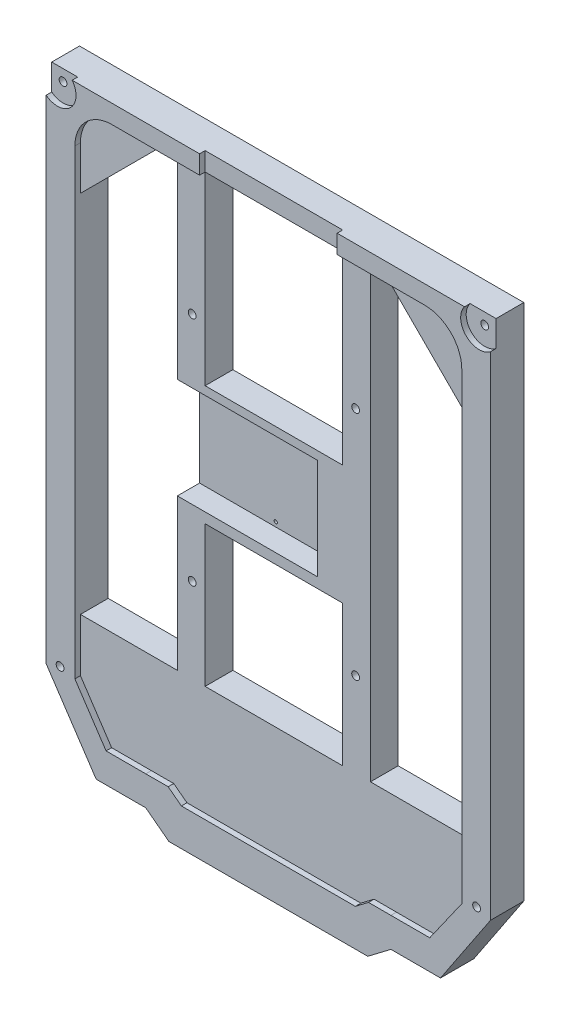
SolidWorks part; units mm, degrees
ref_plane "Front Plane" through (0, 0, 0) normal (0, 0, 1) x (1, 0, 0)
ref_plane "Top Plane" through (0, 0, 0) normal (0, 1, 0) x (1, 0, 0)
ref_plane "Right Plane" through (0, 0, 0) normal (1, 0, 0) x (0, 0, -1)
ref_plane "Plan1" through (0, 0, 30) normal (0, 0, 1) x (1, 0, 0)
sketch "Esquisse1" plane through (0, 0, 30) normal (0, 0, 1) x (1, 0, 0)
  line L0 (33.9438, -122.1178) -> (33.9438, 157.8822)
  line L1 (33.9438, 157.8822) -> (-206.0562, 157.8822)
  line L2 (-206.0562, 157.8822) -> (-206.0562, -122.1178)
  line L3 (-206.0562, -122.1178) -> (-179.0562, -162.6148)
  line L4 (-179.0562, -162.6148) -> (-152.2689, -162.6148)
  line L5 (-152.2689, -162.6148) -> (-139.751, -172.1178)
  line L6 (-139.751, -172.1178) -> (-32.3613, -172.1178)
  line L7 (-32.3613, -172.1178) -> (-19.8434, -162.6148)
  line L8 (-19.8434, -162.6148) -> (6.9438, -162.6148)
  line L9 (6.9438, -162.6148) -> (33.9438, -122.1178)
extrude "Boss.-Extru.1" add sketch "Esquisse1" against normal blind 30
sketch "Esquisse2" plane through (0, 0, 30) normal (0, 0, 1) x (1, 0, 0)
  line L0 (-123.2061, 157.8822) -> (-123.2061, 147.8822)
  line L1 (-123.2061, 147.8822) -> (-190.5562, 147.8822)
  line L2 (-190.5562, 147.8822) -> (-190.5562, -121.432)
  line L3 (-190.5562, -121.432) -> (-173.704, -146.7084)
  line L4 (-173.704, -146.7084) -> (-152.2689, -146.7084)
  line L5 (-152.2689, -146.7084) -> (-140.1758, -146.6851)
  line L6 (-140.1758, -146.6851) -> (-133.0195, -152.1178)
  line L7 (-133.0195, -152.1178) -> (-39.0928, -152.1178)
  line L8 (-39.0928, -152.1178) -> (-31.9365, -146.6851)
  line L9 (-31.9365, -146.6851) -> (-19.8434, -146.7084)
  line L10 (-19.8434, -146.7084) -> (1.1411, -146.7084)
  line L11 (1.1411, -146.7084) -> (18.4438, -122.1178)
  line L12 (18.4438, -122.1178) -> (18.4438, 147.8822)
  line L13 (18.4438, 147.8822) -> (-48.9062, 147.8822)
  line L14 (-48.9062, 147.8822) -> (-48.9062, 157.8822)
  line L15 (-48.9062, 157.8822) -> (-123.2061, 157.8822)
extrude "Enlèv. mat.-Extru.1" cut sketch "Esquisse2" against normal blind 15
sketch "Esquisse3" plane through (0, 0, 0) normal (0, 0, -1) x (-1, 0, 0)
  line L0 (162.5961, 137.8822) -> (162.5961, 147.8822)
  line L1 (162.5961, 147.8822) -> (190.5562, 147.8822)
  line L2 (190.5562, 147.8822) -> (190.5562, 118.9445)
  line L3 (190.5562, 118.9445) -> (180.5562, 118.9445)
  line L4 (180.5562, 118.9445) -> (180.5562, 137.8822)
  line L5 (180.5562, 137.8822) -> (162.5961, 137.8822)
extrude "Boss.-Extru.2" add sketch "Esquisse3" along normal blind 10
sketch "Esquisse4" plane through (0, 0, 0) normal (0, 0, -1) x (-1, 0, 0)
  line L0 (152.2689, -136.7084) -> (168.3524, -136.7084)
  line L1 (168.3524, -136.7084) -> (180.5562, -118.404)
  line L2 (180.5562, -118.404) -> (190.5562, -121.432)
  line L3 (190.5562, -121.432) -> (173.704, -146.7084)
  line L4 (173.704, -146.7084) -> (152.2689, -146.7084)
  line L5 (152.2689, -146.7084) -> (152.2689, -136.7084)
extrude "Boss.-Extru.3" add sketch "Esquisse4" along normal blind 10
sketch "Esquisse5" plane through (0, 0, 0) normal (0, 0, -1) x (-1, 0, 0)
  line L0 (-8.4438, 137.8822) -> (-8.4438, 118.9445)
  line L1 (-8.4438, 118.9445) -> (-18.4438, 118.9445)
  line L2 (-18.4438, 118.9445) -> (-18.4438, 147.8822)
  line L3 (-18.4438, 147.8822) -> (9.5162, 147.8822)
  line L4 (9.5162, 147.8822) -> (9.5162, 137.8822)
  line L5 (9.5162, 137.8822) -> (-8.4438, 137.8822)
extrude "Boss.-Extru.4" add sketch "Esquisse5" along normal blind 10
sketch "Esquisse6" plane through (0, 0, 0) normal (0, 0, -1) x (-1, 0, 0)
  line L0 (3.7599, -136.7084) -> (19.8434, -136.7084)
  line L1 (19.8434, -136.7084) -> (19.8434, -146.7084)
  line L2 (19.8434, -146.7084) -> (-1.1411, -146.7084)
  line L3 (-1.1411, -146.7084) -> (-18.4438, -122.1178)
  line L4 (-18.4438, -122.1178) -> (-8.4438, -118.404)
  line L5 (-8.4438, -118.404) -> (3.7599, -136.7084)
extrude "Boss.-Extru.5" add sketch "Esquisse6" along normal blind 10
hole_wizard "Diamètre du perçage Ø4.2 (4.2)1" positions "Esquisse8" profile "Esquisse7" hole size "Ø4.2" standard "Ansi Metric"
sketch "Esquisse8" plane through (0, 0, 30) normal (0, 0, 1) x (1, 0, 0)
  point P0 (26.4389, -119.6078)
  point P1 (-198.5512, -119.6078)
sketch "Esquisse7" plane through (26.4389, -119.6078, 30) normal (1, 0, 0) x (0, -1, 0)
  line L0 (0, 0) -> (0, 40)
  line L1 (0, 40) -> (2.1, 40)
  line L2 (2.1, 40) -> (2.1, 0)
  line L5 (2.1, 0) -> (0, 0)
  line L11 (0, -6.35) -> (0, 107.95) construction
  dimension "Diamètre du perçage jusqu'au prochain" = 4.2
  dimension "Profondeur du perçage jusqu'au prochain" = 40
hole_wizard "Chambrage pour vis à tête hexagonale M3.51" positions "Esquisse10" profile "Esquisse9" counterbore size "M3.5" standard "Ansi Metric"
sketch "Esquisse10" plane through (0, 0, 30) normal (0, 0, 1) x (1, 0, 0)
  point P0 (-199.9402, 151.7663)
  point P1 (27.8279, 151.7663)
sketch "Esquisse9" plane through (-199.9402, 151.7663, 30) normal (1, 0, 0) x (0, -1, 0)
  line L0 (0, 0) -> (0, 40)
  line L1 (0, 40) -> (2.1, 40)
  line L3 (2.1, 40) -> (2.1, 15)
  line L4 (2.1, 15) -> (10, 15)
  line L5 (10, 15) -> (10, 0)
  line L7 (10, 0) -> (0, 0)
  line L11 (0, -6.35) -> (0, 107.95) construction
  dimension "Diamètre du perçage jusqu'au prochain" = 4.2
  dimension "Profondeur du perçage jusqu'au prochain" = 40
  dimension "Diamètre du chambrage" = 20
  dimension "Profondeur du chambrage" = 15
fillet "Congé1" radius 10 2 edges at (-180.5562, 137.8822, -5) (8.4438, 137.8822, -5)
fillet "Congé2" radius 20 4 edges at (-190.5562, 147.8822, 22.5) (18.4438, 147.8822, -5) (18.4438, 147.8822, 22.5) (-190.5562, 147.8822, -5)
sketch "Esquisse11" plane through (0, 0, 15) normal (0, 0, 1) x (1, 0, 0)
  line L0 (-123.2061, 147.8822) -> (-123.2061, 47.8822)
  line L1 (-138.2061, 147.8822) -> (-138.2061, 57.8822)
  line L2 (-123.2061, 47.8822) -> (-190.5562, -22.4359)
  line L3 (-138.2061, 57.8822) -> (-190.5562, 3.2251)
  line L4 (-33.9062, 57.8822) -> (18.4438, 3.2251)
  line L5 (-33.9062, 147.8822) -> (-33.9062, 57.8822)
  line L6 (-48.9062, 147.8822) -> (-48.9062, 47.8822)
  line L7 (-48.9062, 47.8822) -> (18.4438, -22.4359)
  line L8 (-146.8811, 147.8822) -> (-190.5562, 104.2072)
  line L9 (18.4438, -22.4359) -> (18.4438, -92.768)
  line L10 (-25.2312, 147.8822) -> (18.4438, 104.2072)
  line L12 (-190.5562, -92.768) -> (18.4438, -92.768)
  line L13 (-190.5562, -22.4359) -> (-190.5562, -92.768)
  line L15 (18.4438, 95.5321) -> (18.4438, 3.2251)
  line L16 (-190.5562, 3.2251) -> (-190.5562, 95.5321)
  line L17 (-123.2061, 147.8822) -> (-48.9062, 147.8822)
  line L22 (-190.5562, 104.2072) -> (-190.5562, 95.5321)
  line L23 (-146.8811, 147.8822) -> (-138.2061, 147.8822)
  line L24 (-33.9062, 147.8822) -> (-25.2312, 147.8822)
  line L25 (18.4438, 104.2072) -> (18.4438, 95.5321)
  line L28 (-86.0562, 157.8822) -> (-86.0562, -181.6692) construction
  line L29 (-48.9062, 157.8822) -> (-123.2061, 157.8822) construction
extrude "Enlèv. mat.-Extru.2" cut sketch "Esquisse11" against normal through all
hole_wizard "Trou taraudé M5x0.81" positions "Esquisse3D1" profile "Esquisse12" tap size "M5x0.8" standard "Ansi Metric" end condition through all
sketch3d "Esquisse3D1"
  line L0 (-199.9402, 151.7663, 0) -> (-199.9402, 151.7663, 15) construction
  line L1 (27.8279, 151.7663, 0) -> (27.8279, 151.7663, 15) construction
  line L2 (26.4389, -119.6078, 0) -> (26.4389, -119.6078, 30) construction
  line L3 (-198.5512, -119.6078, 0) -> (-198.5512, -119.6078, 30) construction
  point P0 (-199.9402, 151.7663, 15)
  point P4 (27.8279, 151.7663, 15)
  point P8 (26.4389, -119.6078, 30)
  point P12 (-198.5512, -119.6078, 30)
sketch "Esquisse12" plane through (-199.9402, 151.7663, 15) normal (1, 0, 0) x (0, -1, 0)
  line L0 (0, 0) -> (0, 25)
  line L1 (0, 25) -> (2.1, 25)
  line L2 (2.1, 25) -> (2.1, 0)
  line L5 (2.1, 0) -> (0, 0)
  line L11 (0, -6.35) -> (0, 107.95) construction
  dimension "Diamètre du trou pour taraudage jusqu'au prochain" = 4.2
  dimension "Profondeur du trou pour taraudage jusqu'au prochain" = 25
cosmetic thread "Filetage de perçage1" parameters "D2"=5
cosmetic thread "Filetage de perçage2" parameters "D2"=5
cosmetic thread "Filetage de perçage5" parameters "D2"=5
cosmetic thread "Filetage de perçage6" parameters "D2"=5
sketch "Esquisse13" plane through (0, 0, 15) normal (0, 0, 1) x (1, 0, 0)
  line L0 (-48.9062, 47.8822) -> (-123.2061, 47.8822)
  line L1 (18.4438, -22.4359) -> (-48.9062, 47.8822) construction
  line L2 (-123.2061, 47.8822) -> (-148.9061, 21.0497)
  line L3 (-123.2061, 47.8822) -> (-190.5562, -22.4359) construction
  line L4 (-123.2061, 21.0497) -> (-48.9062, 21.0497)
  line L9 (-23.2063, 21.0497) -> (-48.9062, 47.8822)
  line L10 (18.4438, -49.2685) -> (18.4438, -22.4359)
  line L15 (-86.0562, 157.8822) -> (-86.0562, -186.9607) construction
  line L16 (-48.9062, 157.8822) -> (-123.2061, 157.8822) construction
  line L17 (-148.9061, 21.0497) -> (-190.5562, -22.4359)
  line L18 (-123.2061, 21.0497) -> (-190.5562, -49.2685)
  line L19 (-190.5562, 127.8822) -> (-190.5562, -121.432) construction
  line L20 (-190.5562, -49.2685) -> (-190.5562, -22.4359)
  line L21 (-23.2063, 21.0497) -> (18.4438, -22.4359)
  line L22 (-48.9062, 21.0497) -> (18.4438, -49.2685)
extrude "Boss.-Extru.6" add sketch "Esquisse13" against normal up to surface (15 mm away) up to face at (-11.2312, 92.2158, 0)
sketch "Esquisse14" plane through (0, 0, 30) normal (0, 0, 1) x (1, 0, 0)
  line L1 (-249.2636, 174.2987) -> (95.3604, 174.2987)
  line L2 (-249.2636, 174.2987) -> (-249.2636, -190.5575)
  line L3 (-249.2636, -190.5575) -> (95.3604, -190.5575)
  line L4 (95.3604, 174.2987) -> (95.3604, -190.5575)
extrude "Enlèv. mat.-Extru.3" cut sketch "Esquisse14" against normal blind 12
sketch "Esquisse15" plane through (0, 0, 15) normal (0, 0, 1) x (1, 0, 0)
  line L2 (-165.2407, 11.9495) -> (-165.2407, -16.6719)
  line L3 (-165.2407, -16.6719) -> (-10.3735, -16.6719)
  line L4 (-10.3735, 17.0806) -> (-10.3735, -16.6719)
  line L5 (-165.2407, 11.9495) -> (-140.9844, 36.2058)
  line L6 (-140.9844, 36.2058) -> (-29.4987, 36.2058)
  line L7 (-29.4987, 36.2058) -> (-10.3735, 17.0806)
extrude "Boss.-Extru.7" add sketch "Esquisse15" against normal up to surface (15 mm away)
sketch "Esquisse16" plane through (0, 0, 15) normal (0, 0, 1) x (1, 0, 0)
  line L0 (-86.0562, 157.8822) -> (-86.0562, -189.4449) construction
  line L1 (-48.9062, 157.8822) -> (-123.2061, 157.8822) construction
  line L3 (-109.5562, 43.3493) -> (-62.5562, 43.3493)
  line L4 (-109.5562, 43.3493) -> (-109.5562, -11.1507)
  line L5 (-109.5562, -11.1507) -> (-62.5562, -11.1507)
  line L6 (-62.5562, 43.3493) -> (-62.5562, -11.1507)
  line L7 (-109.5562, 43.3493) -> (-62.5562, -11.1507) construction
  line L8 (-109.5562, -11.1507) -> (-62.5562, 43.3493) construction
  point P4 (-86.0562, 16.0993)
  dimension "D1" = 54.5
  dimension "D2" = 47
extrude "Enlèv. mat.-Extru.4" cut sketch "Esquisse16" against normal blind 12
sketch "Esquisse17" plane through (0, 0, 3) normal (0, 0, 1) x (1, 0, 0)
  line L0 (-86.0562, 43.3493) -> (-86.0562, -11.1507) construction
  line L1 (-62.5562, 43.3493) -> (-109.5562, 43.3493) construction
  line L2 (-109.5562, -11.1507) -> (-62.5562, -11.1507) construction
  line L3 (-109.5562, 16.0993) -> (-62.5562, 16.0993) construction
  line L4 (-109.5562, 43.3493) -> (-109.5562, -11.1507) construction
  line L5 (-62.5562, -11.1507) -> (-62.5562, 43.3493) construction
  line L6 (-97.0612, 50.1985) -> (-97.0612, -29.2943) construction
  line L7 (-109.2012, 43.0993) -> (-62.9112, 43.0993)
  line L8 (-109.2012, 43.0993) -> (-109.2012, -10.9007)
  line L9 (-109.2012, -10.9007) -> (-62.9112, -10.9007)
  line L10 (-62.9112, 43.0993) -> (-62.9112, -10.9007) construction
  line L11 (-109.2012, 43.0993) -> (-62.9112, -10.9007) construction
  line L12 (-109.2012, -10.9007) -> (-62.9112, 43.0993) construction
  circle A4 centre (-65.1412, 16.0993) radius 2.23 construction
  circle A5 centre (-97.0612, -8.6707) radius 2.23 construction
  circle A6 centre (-97.0612, 40.8693) radius 2.23 construction
  circle A7 centre (-97.0612, 40.8693) radius 0.5
  circle A8 centre (-97.0612, -8.6707) radius 0.5
  circle A9 centre (-65.1412, 16.0993) radius 0.5
  point P12 (-86.0562, 16.0993)
  point P13 (-86.0562, 16.0993)
  dimension "D3" = 1
  dimension "D4" = 31.92
  dimension "D5" = 4.46
  dimension "D6" = 4.46
  dimension "D7" = 1
  dimension "D8" = 1
  dimension "D9" = 4.46
  dimension "D1" = 46.29
  dimension "D2" = 54
extrude "Enlèv. mat.-Extru.5" cut sketch "Esquisse17" against normal blind 12 contours A7 | A9 | A8
hole_wizard "Trou taraudé M2.2x0.451" positions "Esquisse3D2" profile "Esquisse18" tap size "M2.2x0.45" standard "Ansi Metric" end condition through all
sketch3d "Esquisse3D2"
  line L0 (-97.0612, 40.8693, 0) -> (-97.0612, 40.8693, 3) construction
  line L1 (-65.1412, 16.0993, 0) -> (-65.1412, 16.0993, 3) construction
  line L2 (-97.0612, -8.6707, 0) -> (-97.0612, -8.6707, 3) construction
  point P0 (-97.0612, 40.8693, 3)
  point P4 (-65.1412, 16.0993, 3)
  point P8 (-97.0612, -8.6707, 3)
sketch "Esquisse18" plane through (-97.0612, 40.8693, 3) normal (1, 0, 0) x (0, -1, 0)
  line L0 (0, 0) -> (0, 13)
  line L1 (0, 13) -> (0.875, 13)
  line L2 (0.875, 13) -> (0.875, 0)
  line L5 (0.875, 0) -> (0, 0)
  line L11 (0, -6.35) -> (0, 107.95) construction
  dimension "Diamètre du trou pour taraudage jusqu'au prochain" = 1.75
  dimension "Profondeur du trou pour taraudage jusqu'au prochain" = 13
cosmetic thread "Filetage de perçage7" parameters "D2"=2.2
cosmetic thread "Filetage de perçage8" parameters "D2"=2.2
cosmetic thread "Filetage de perçage9" parameters "D2"=2.2
sketch "Esquisse19" plane through (0, 0, 15) normal (0, 0, 1) x (1, 0, 0)
  line L0 (-138.2061, 57.8822) -> (-138.2061, -92.768)
  line L1 (-190.5562, -92.768) -> (18.4438, -92.768) construction
  line L2 (-123.2061, -92.768) -> (-123.2061, 67.1881) construction
  line L3 (-123.2061, 147.8822) -> (-123.2061, 47.8822) construction
  line L4 (-138.2061, -92.768) -> (-123.2061, -92.768)
  line L5 (-190.5562, -121.432) -> (-190.5562, 127.8822) construction
  line L6 (-190.5562, 57.8822) -> (-138.2061, 57.8822)
  line L7 (-190.5562, 57.8822) -> (-190.5562, -92.768)
  line L8 (-190.5562, -92.768) -> (-138.2061, -92.768)
  line L9 (-138.2061, 57.8822) -> (-138.2061, -92.768)
  line L10 (-86.0562, 43.3493) -> (-86.0562, -182.6033) construction
  line L11 (-62.5562, 43.3493) -> (-109.5562, 43.3493) construction
  line L12 (-48.9062, -92.768) -> (-48.9062, 67.1881) construction
  line L13 (18.4438, -92.768) -> (-33.9062, -92.768)
  line L14 (-33.9062, 57.8822) -> (-33.9062, -92.768)
  line L15 (18.4438, 57.8822) -> (-33.9062, 57.8822)
  line L16 (18.4438, 57.8822) -> (18.4438, -92.768)
  line M16 (-190.5562, -49.2685) -> (-159.3355, -16.6719)
  line M17 (-159.3355, -16.6719) -> (-12.7768, -16.6719)
  line M18 (-12.7768, -16.6719) -> (18.4438, -49.2685)
  line M19 (18.4438, -49.2685) -> (18.4438, 3.2251)
  line M20 (18.4438, 3.2251) -> (-33.9062, 57.8822)
  line M28 (-138.2061, 57.8822) -> (-190.5562, 3.2251)
  line M29 (-190.5562, 3.2251) -> (-190.5562, -49.2685)
extrude "Enlèv. mat.-Extru.6" cut sketch "Esquisse19" against normal through all contours L7 L8 L0 M17 M16 | L6 L7 M28 | L0 M28 M29 M16 M17 | L16 L15 M20 | L14 M20 M17 M18 M19 | L16 L14 L13 M18 M17
sketch "Esquisse20" plane through (0, 0, 15) normal (0, 0, 1) x (1, 0, 0)
  line L0 (-138.2061, -16.6719) -> (-138.2061, -97.0392)
  line L1 (-138.2061, -97.0392) -> (-123.2061, -97.0392)
  line L2 (-123.2061, -97.0392) -> (-123.2061, 49.8921)
  line L3 (-123.2061, 147.8822) -> (-123.2061, 47.8822) construction
  line L4 (-123.2061, 49.8921) -> (-138.2061, 49.8921)
  line L5 (-138.2061, -16.6719) -> (-138.2061, 147.8822) construction
  line L6 (-138.2061, 49.8921) -> (-138.2061, -16.6719)
  line L7 (-86.0562, -16.6719) -> (-86.0562, -182.4646) construction
  line L8 (-138.2061, -16.6719) -> (-33.9062, -16.6719) construction
  line L9 (-48.9062, 49.8921) -> (-33.9062, 49.8921)
  line L10 (-48.9062, -97.0392) -> (-48.9062, 49.8921)
  line L11 (-33.9062, -97.0392) -> (-48.9062, -97.0392)
  line L12 (-33.9062, -16.6719) -> (-33.9062, -97.0392)
  line L13 (-33.9062, 49.8921) -> (-33.9062, -16.6719)
extrude "Boss.-Extru.8" add sketch "Esquisse20" against normal up to surface (15 mm away) up to face at (-97.9362, 40.8693, 0)
sketch "Esquisse21" plane through (0, 0, 15) normal (0, 0, 1) x (1, 0, 0)
  line L0 (-109.5562, -11.1507) -> (-62.5562, -11.1507) construction
  line L1 (-109.5562, 43.3493) -> (-143.574, 43.3493)
  line L2 (-109.5562, 43.3493) -> (-109.5562, -11.1507)
  line L3 (-109.5562, -11.1507) -> (-143.574, -11.1507)
  line L4 (-143.574, 43.3493) -> (-143.574, -11.1507)
extrude "Enlèv. mat.-Extru.7" cut sketch "Esquisse21" against normal up to surface (12 mm away) up to face at (-96.1862, 40.8693, 3)
sketch "Esquisse22" plane through (0, 0, 15) normal (0, 0, 1) x (1, 0, 0)
  line L0 (-48.9062, 47.8822) -> (-123.2061, 47.8822) construction
  line L1 (-86.0562, 47.8822) -> (-86.0562, 101.6) construction
  line L2 (-123.2061, 147.8822) -> (-123.2061, 47.8822) construction
  line L4 (-62.5562, 16.0993) -> (72.4739, 16.0993) construction
  line L5 (-62.5562, -11.1507) -> (-62.5562, 43.3493) construction
  point P0 (-130.2061, 77.8822)
  point P6 (-41.9062, 77.8822)
  point P14 (-41.9062, -47.1178)
  point P15 (-130.2061, -47.1178)
  dimension "D1" = 30
  dimension "D2" = 7
  dimension "D3" = 95
hole_wizard "Trou taraudé M5x0.82" positions "Esquisse3D3" profile "Esquisse23" tap size "M5x0.8" standard "Ansi Metric"
sketch3d "Esquisse3D3"
  point P0 (-130.2061, 77.8822, 15)
  point P3 (-41.9062, 77.8822, 15)
sketch "Esquisse23" plane through (-130.2061, 77.8822, 15) normal (1, 0, 0) x (0, -1, 0)
  line L0 (0, 0) -> (0, 56.1888)
  line L1 (0, 56.1888) -> (2.1, 54.927)
  line L2 (2.1, 54.927) -> (2.1, 0)
  line L5 (2.1, 0) -> (0, 0)
  line L10 (0, 56.1888) -> (-2.1, 54.927) construction
  line L11 (0, -6.35) -> (0, 107.95) construction
  dimension "Diamètre du trou pour taraudage" = 4.2
  dimension "Profondeur du trou pour taraudage" = 54.927
  dimension "Angle de pointe" = 118
cosmetic thread "Filetage de perçage10" parameters "D1"=50.927, "D2"=5
cosmetic thread "Filetage de perçage11" parameters "D1"=50.927, "D2"=5
hole_wizard "Trou taraudé M5x0.84" positions "Esquisse3D5" profile "Esquisse25" tap size "M5x0.8" standard "Ansi Metric"
sketch3d "Esquisse3D5"
  point P0 (-130.2061, -47.1178, 15)
  point P3 (-41.9062, -47.1178, 15)
sketch "Esquisse25" plane through (-130.2061, -47.1178, 15) normal (1, 0, 0) x (0, -1, 0)
  line L0 (0, 0) -> (0, 56.1888)
  line L1 (0, 56.1888) -> (2.1, 54.927)
  line L2 (2.1, 54.927) -> (2.1, 0)
  line L5 (2.1, 0) -> (0, 0)
  line L10 (0, 56.1888) -> (-2.1, 54.927) construction
  line L11 (0, -6.35) -> (0, 107.95) construction
  dimension "Diamètre du trou pour taraudage" = 4.2
  dimension "Profondeur du trou pour taraudage" = 54.927
  dimension "Angle de pointe" = 118
cosmetic thread "Filetage de perçage14" parameters "D1"=50.927, "D2"=5
cosmetic thread "Filetage de perçage15" parameters "D1"=50.927, "D2"=5
